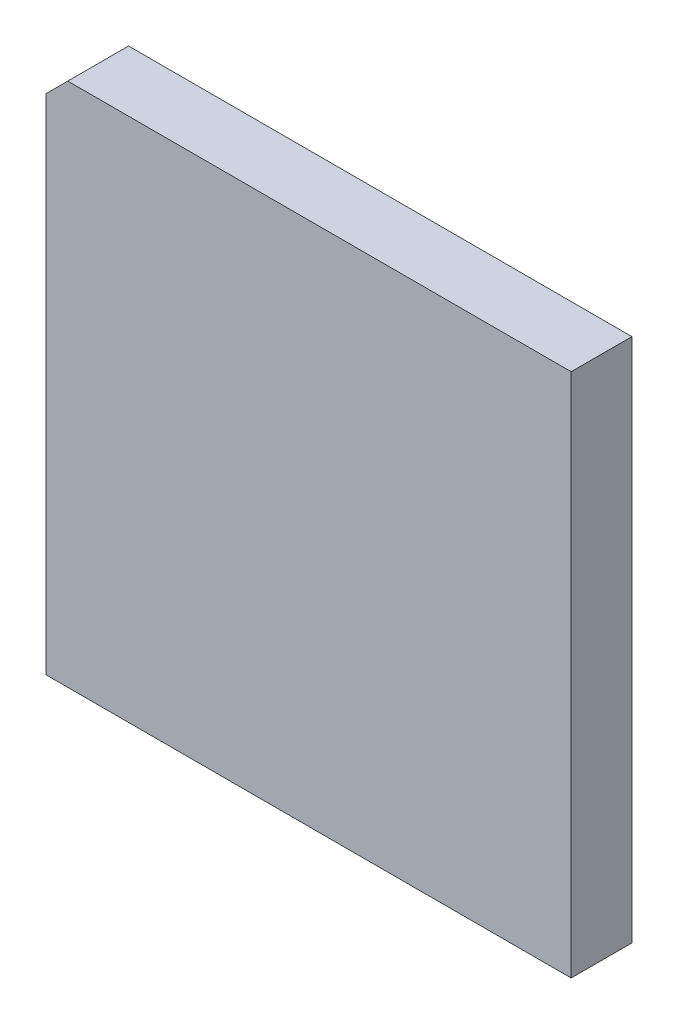
SolidWorks part; units mm, degrees
ref_plane "前视基准面" through (0, 0, 0) normal (0, 0, 1) x (1, 0, 0)
ref_plane "上视基准面" through (0, 0, 0) normal (0, 1, 0) x (1, 0, 0)
ref_plane "右视基准面" through (0, 0, 0) normal (1, 0, 0) x (0, 0, -1)
sketch "草图1" plane through (0, 0, 0) normal (0, 0, 1) x (1, 0, 0)
  line L0 (-5.55, 6.05) -> (-6.05, 5.55)
  line L1 (-6.05, 5.55) -> (-6.05, -6.05)
  line L2 (-6.05, -6.05) -> (6.05, -6.05)
  line L3 (6.05, -6.05) -> (6.05, 6.05)
  line L4 (6.05, 6.05) -> (-5.55, 6.05)
extrude "Component_Outline" add sketch "草图1" along normal blind 1.4 separate body
sketch3d "3D草图1"
  line L0 (0, 0, 0) -> (1, 0, 0)
  line L1 (0, 0, 0) -> (0, 1, 0)
  line L2 (0, 0, 0) -> (0, 0, 1)
  point P0 (0, 0, 0)
